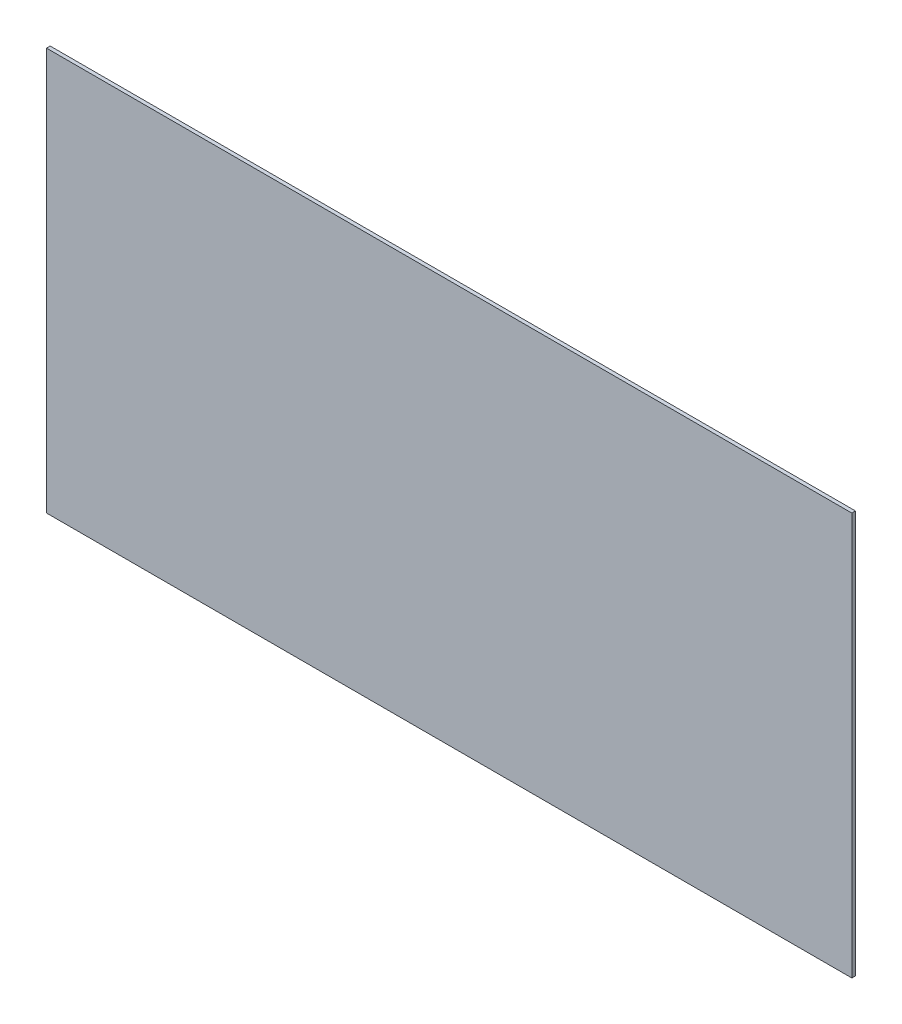
SolidWorks part; units mm, degrees
ref_plane "Front Plane" through (0, 0, 0) normal (0, 0, 1) x (1, 0, 0)
ref_plane "Top Plane" through (0, 0, 0) normal (0, 1, 0) x (1, 0, 0)
ref_plane "Right Plane" through (0, 0, 0) normal (1, 0, 0) x (0, 0, -1)
sketch "Sketch1" plane through (0, 0, 0) normal (0, 0, 1) x (1, 0, 0)
  line L1 (1100, -550) -> (-1100, -550)
  line L2 (1100, -550) -> (1100, 550)
  line L3 (1100, 550) -> (-1100, 550)
  line L4 (-1100, -550) -> (-1100, 550)
  line L5 (1100, -550) -> (-1100, 550) construction
  line L6 (1100, 550) -> (-1100, -550) construction
  point P0 (0, 0)
  dimension "D1" = 1100
  dimension "D2" = 2200
extrude "Boss-Extrude1" add sketch "Sketch1" along normal mid plane 10
